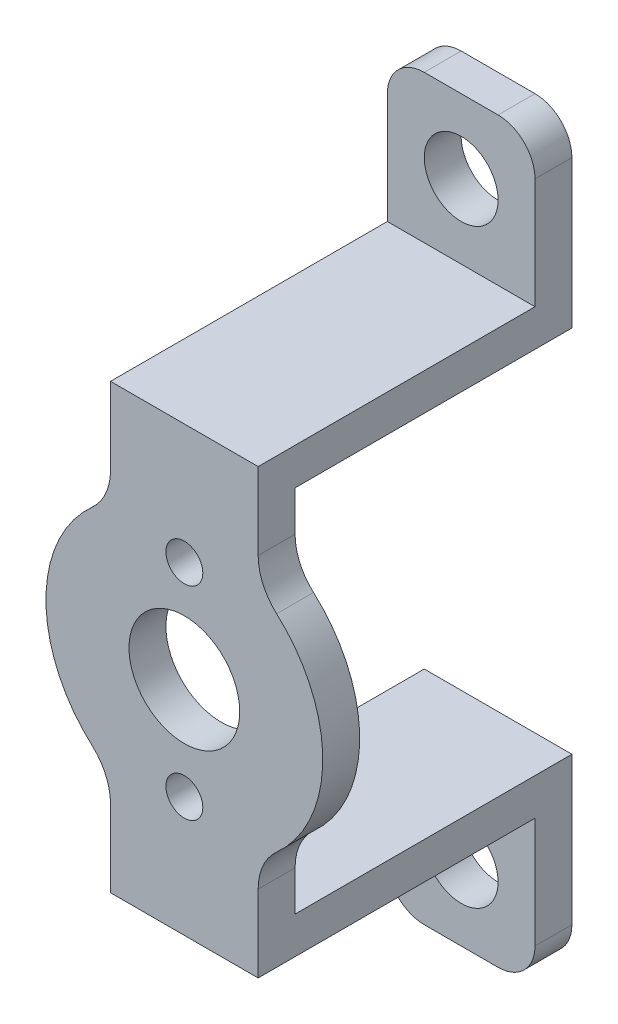
SolidWorks part; units mm, degrees
material "6061 合金"
ref_plane "前视基准面" through (0, 0, 0) normal (0, 0, 1) x (1, 0, 0)
ref_plane "上视基准面" through (0, 0, 0) normal (0, 1, 0) x (1, 0, 0)
ref_plane "右视基准面" through (0, 0, 0) normal (1, 0, 0) x (0, 0, -1)
sketch "草图1" plane through (0, 0, 0) normal (0, 0, 1) x (1, 0, 0)
  line L1 (-4, -10) -> (4, -10)
  line L2 (-4, -10) -> (-4, 10)
  line L3 (-4, 10) -> (4, 10)
  line L4 (4, -10) -> (4, 10)
  line L5 (-4, -10) -> (4, 10) construction
  line L6 (-4, 10) -> (4, -10) construction
  circle A0 centre (0, 0) radius 2
  circle A1 centre (0, 0) radius 7.5
  dimension "D1" = 20
  dimension "D2" = 8
extrude "凸台-拉伸1" add sketch "草图1" along normal blind 2 contours L4 A1 | L4 A1 L2 A0 | L2 A1 | A1 L4 L3 L2 | A1 L2 L1 L4
sketch "草图4" plane through (0, 0, 2) normal (0, 0, 1) x (1, 0, 0)
  line L5 (-4, -10) -> (4, -10)
  line L6 (-4, -10) -> (-4, -12)
  line L7 (-4, -12) -> (4, -12)
  line L8 (4, -10) -> (4, -12)
  line L9 (-4, 10) -> (4, 10)
  line L10 (-4, 10) -> (-4, 12)
  line L11 (-4, 12) -> (4, 12)
  line L12 (4, 10) -> (4, 12)
  dimension "D1" = 2
  dimension "D2" = 8
  dimension "D3" = 2
  dimension "D4" = 8
extrude "凸台-拉伸3" add sketch "草图4" against normal blind 15
sketch "草图5" plane through (0, 0, 0) normal (0, 0, -1) x (-1, 0, 0)
  circle A0 centre (0, 0) radius 5.5 construction
  circle A1 centre (0, 5.5) radius 1
  circle A2 centre (0, -5.5) radius 1
extrude "切除-拉伸1" cut sketch "草图5" against normal blind 8
sketch "草图6" plane through (0, 0, -13) normal (0, 0, -1) x (-1, 0, 0)
  line L5 (-4, -10) -> (4, -10)
  line L6 (-4, -10) -> (-4, -20)
  line L7 (-4, -20) -> (4, -20)
  line L8 (4, -10) -> (4, -20)
  line L9 (-4, 10) -> (4, 10)
  line L10 (-4, 10) -> (-4, 20)
  line L11 (-4, 20) -> (4, 20)
  line L12 (4, 10) -> (4, 20)
  dimension "D1" = 10
  dimension "D2" = 8
  dimension "D3" = 10
  dimension "D4" = 8
extrude "凸台-拉伸4" add sketch "草图6" along normal blind 2
sketch "草图7" plane through (0, 0, -13) normal (0, 0, 1) x (1, 0, 0)
  circle A0 centre (0, 0) radius 16 construction
  circle A1 centre (0, 16) radius 2
  circle A2 centre (0, -16) radius 2
extrude "切除-拉伸2" cut sketch "草图7" against normal blind 2
fillet "圆角1" radius 3 4 edges at (-4, -6.3443, 1) (-4, 6.3443, 1) (4, -6.3443, 1) (4, 6.3443, 1)
fillet "圆角2" radius 2 4 edges at (-4, -20, -14) (4, -20, -14) (4, 20, -14) (-4, 20, -14)
sketch "草图9" plane through (0, 0, 2) normal (0, 0, 1) x (1, 0, 0)
  circle A0 centre (0, 0) radius 3
  dimension "D1" = 6
extrude "切除-拉伸3" cut sketch "草图9" against normal blind 10
